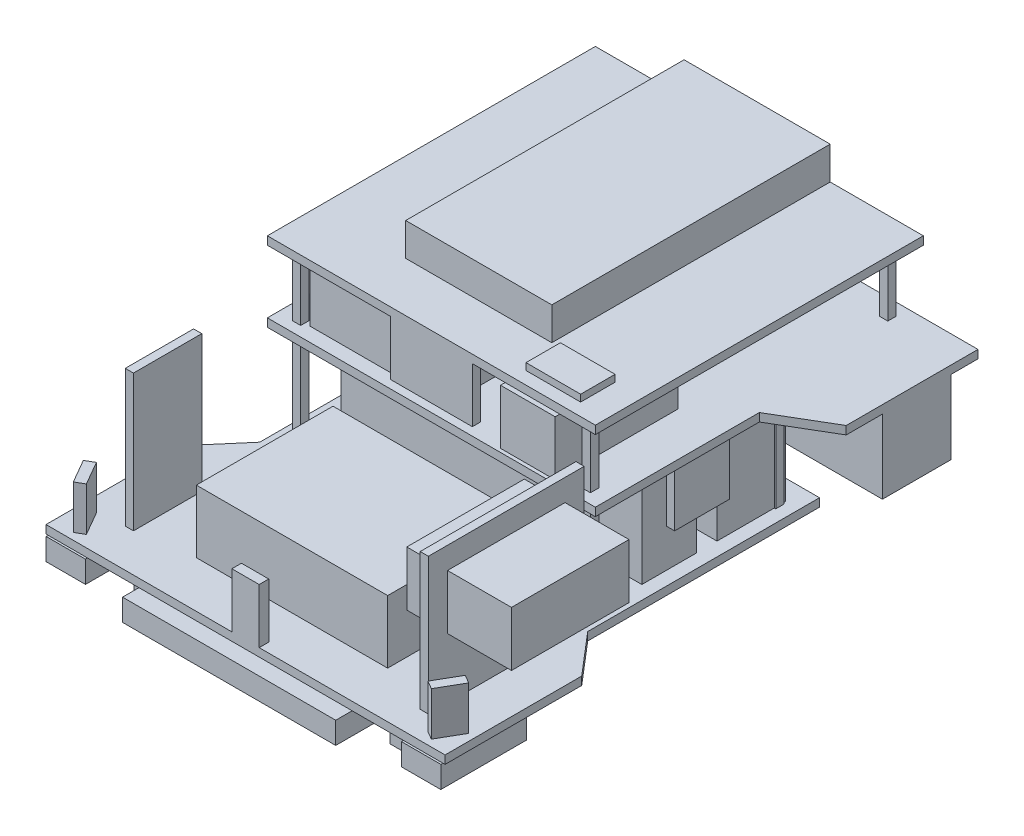
SolidWorks part; units mm, degrees
ref_plane "Front Plane" through (0, 0, 0) normal (0, 0, 1) x (1, 0, 0)
ref_plane "Top Plane" through (0, 0, 0) normal (0, 1, 0) x (1, 0, 0)
ref_plane "Right Plane" through (0, 0, 0) normal (1, 0, 0) x (0, 0, -1)
sketch "Sketch1" plane through (0, 0, 0) normal (0, 1, 0) x (1, 0, 0)
  line L0 (-73, -25) -> (-60, -9.8013)
  line L1 (60, -75) -> (-60, -75)
  line L2 (60, -9.8013) -> (60, 75)
  line L3 (60, 75) -> (-60, 75)
  line L4 (-60, -9.8013) -> (-60, 75)
  line L5 (60, -75) -> (-60, 75) construction
  line L6 (60, 75) -> (-60, -75) construction
  line L7 (0, 0) -> (0, -75) construction
  line L9 (-60, -75) -> (-73, -75)
  line L10 (-73, -25) -> (-73, -75)
  line L11 (60, -75) -> (73, -75)
  line L12 (73, -25) -> (73, -75)
  line L13 (73, -25) -> (60, -9.8013)
  point P0 (0, 0)
  dimension "D1" = 150
  dimension "D2" = 120
  dimension "D3" = 50
  dimension "D4" = 13
  dimension "D5" = 20
extrude "Boss-Extrude1" add sketch "Sketch1" along normal blind 3
sketch "Sketch2" plane through (0, 3, 0) normal (0, 1, 0) x (1, 0, 0)
  line L0 (0, 0) -> (0, 75) construction
  line L1 (60, 75) -> (-60, 75) construction
  line L2 (-60, 75) -> (-60, -9.8013) construction
  line L4 (-54.525, -3.335) -> (-51.475, -3.335)
  line L5 (-54.525, -3.335) -> (-54.525, -0.285)
  line L6 (-54.525, -0.285) -> (-51.475, -0.285)
  line L7 (-51.475, -3.335) -> (-51.475, -0.285)
  line L8 (-54.525, -3.335) -> (-51.475, -0.285) construction
  line L9 (-54.525, -0.285) -> (-51.475, -3.335) construction
  line L10 (51.475, -3.335) -> (54.525, -3.335)
  line L11 (51.475, -3.335) -> (51.475, -0.285)
  line L12 (51.475, -0.285) -> (54.525, -0.285)
  line L13 (54.525, -3.335) -> (54.525, -0.285)
  line L14 (51.475, -3.335) -> (54.525, -0.285) construction
  line L15 (51.475, -0.285) -> (54.525, -3.335) construction
  line L16 (52.475, 63.475) -> (55.525, 63.475)
  line L17 (52.475, 63.475) -> (52.475, 66.525)
  line L18 (52.475, 66.525) -> (55.525, 66.525)
  line L19 (55.525, 63.475) -> (55.525, 66.525)
  line L20 (52.475, 63.475) -> (55.525, 66.525) construction
  line L21 (52.475, 66.525) -> (55.525, 63.475) construction
  line L22 (-55.525, 63.475) -> (-52.475, 63.475)
  line L23 (-55.525, 63.475) -> (-55.525, 66.525)
  line L24 (-55.525, 66.525) -> (-52.475, 66.525)
  line L25 (-52.475, 63.475) -> (-52.475, 66.525)
  line L26 (-55.525, 63.475) -> (-52.475, 66.525) construction
  line L27 (-55.525, 66.525) -> (-52.475, 63.475) construction
  circle A0 centre (-53, -1.81) radius 1.525 construction
  circle A1 centre (-54, 65) radius 1.525 construction
  circle A2 centre (53, -1.81) radius 1.525 construction
  circle A3 centre (54, 65) radius 1.525 construction
  dimension "D1" = 10
  dimension "D2" = 3.05
  dimension "D3" = 6
  dimension "D4" = 3.05
  dimension "D5" = 7
  dimension "D6" = 66.81
extrude "Boss-Extrude2" add sketch "Sketch2" along normal blind 35
sketch "Sketch3" plane through (0, 38, 0) normal (0, 1, 0) x (1, 0, 0)
  line L0 (0, 52.99) -> (0, 112.99) construction
  line L1 (-60, -7.01) -> (60, -7.01)
  line L2 (-60, -7.01) -> (-60, 112.99)
  line L3 (-60, 112.99) -> (60, 112.99)
  line L4 (60, -7.01) -> (60, 112.99)
  line L5 (-60, -7.01) -> (60, 112.99) construction
  line L6 (-60, 112.99) -> (60, -7.01) construction
  line L7 (-60, 112.99) -> (-80, 112.99)
  line L8 (-80, 112.99) -> (-80, 64.7803)
  line L9 (-80, 64.7803) -> (-60, 52.99)
  line L10 (80, 64.7803) -> (60, 52.99)
  line L11 (80, 112.99) -> (80, 64.7803)
  line L12 (60, 112.99) -> (80, 112.99)
  line L14 (-54.525, -0.285) -> (-54.525, -3.335) construction
  point P0 (0, 52.99)
  point P19 (-54.525, -1.81)
  dimension "D1" = 120
  dimension "D2" = 120
  dimension "D3" = 60
  dimension "D4" = 30.52
  dimension "D5" = 20
  dimension "D6" = 5.2
extrude "Boss-Extrude3" add sketch "Sketch3" along normal blind 3 contours L8 L9 L2 L7 | L1 L4 L3 L2 | L12 L4 L10 L11
sketch "Sketch4" plane through (0, 41, 0) normal (0, 1, 0) x (1, 0, 0)
  line L0 (0, 0) -> (0, 32.3428) construction
  line L1 (-54.525, -3.335) -> (-51.475, -3.335)
  line L2 (-54.525, -3.335) -> (-54.525, -0.285)
  line L3 (-54.525, -0.285) -> (-51.475, -0.285)
  line L4 (-51.475, -3.335) -> (-51.475, -0.285)
  line L5 (-54.525, -3.335) -> (-51.475, -0.285) construction
  line L6 (-54.525, -0.285) -> (-51.475, -3.335) construction
  line L7 (-60, -7.01) -> (60, -7.01) construction
  line L8 (-60, -7.01) -> (-60, 52.99) construction
  line L9 (80, 112.99) -> (-80, 112.99) construction
  line L10 (-54.525, 105.465) -> (-51.475, 105.465)
  line L11 (-54.525, 105.465) -> (-54.525, 108.515)
  line L12 (-54.525, 108.515) -> (-51.475, 108.515)
  line L13 (-51.475, 105.465) -> (-51.475, 108.515)
  line L14 (-54.525, 105.465) -> (-51.475, 108.515) construction
  line L15 (-54.525, 108.515) -> (-51.475, 105.465) construction
  line L16 (54.525, -0.285) -> (51.475, -3.335) construction
  line L17 (54.525, -3.335) -> (51.475, -0.285) construction
  line L18 (51.475, -3.335) -> (51.475, -0.285)
  line L19 (54.525, -0.285) -> (51.475, -0.285)
  line L20 (54.525, -3.335) -> (54.525, -0.285)
  line L21 (54.525, -3.335) -> (51.475, -3.335)
  line L22 (54.525, 108.515) -> (51.475, 105.465) construction
  line L23 (54.525, 105.465) -> (51.475, 108.515) construction
  line L24 (51.475, 105.465) -> (51.475, 108.515)
  line L25 (54.525, 108.515) -> (51.475, 108.515)
  line L26 (54.525, 105.465) -> (54.525, 108.515)
  line L27 (54.525, 105.465) -> (51.475, 105.465)
  point P0 (-53, -1.81)
  point P12 (-53, 106.99)
  point P24 (53, -1.81)
  point P29 (53, 106.99)
  dimension "D1" = 3.05
  dimension "D2" = 5.2
  dimension "D3" = 7
  dimension "D4" = 6
extrude "Boss-Extrude4" add sketch "Sketch4" along normal blind 23
sketch "Sketch6" plane through (0, 64, 0) normal (0, 1, 0) x (1, 0, 0)
  line L0 (60, -7.01) -> (-60, -7.01)
  line L1 (60, -7.01) -> (60, 112.99)
  line L2 (-60, -7.01) -> (-60, 112.99)
  line L3 (60, 112.99) -> (-60, 112.99)
  line L4 (80, 112.99) -> (-80, 112.99) construction
extrude "Boss-Extrude5" add sketch "Sketch6" along normal blind 3
sketch "Sketch7" plane through (0, 38, 0) normal (0, -1, 0) x (1, 0, 0)
  line L0 (-80, -78.03) -> (-80, -103.03)
  line L1 (-80, -78.03) -> (-12, -78.03)
  line L2 (-80, -103.03) -> (-12, -103.03)
  line L3 (-12, -78.03) -> (-12, -103.03)
  line L4 (-80, -112.99) -> (-80, -64.7803) construction
  line L5 (0, 0) -> (0, -39.6137) construction
  line L6 (12, -78.03) -> (12, -103.03)
  line L7 (80, -103.03) -> (12, -103.03)
  line L8 (80, -78.03) -> (12, -78.03)
  line L9 (80, -78.03) -> (80, -103.03)
  line L10 (80, -112.99) -> (-80, -112.99) construction
  point P13 (-80, -90.53)
  dimension "D1" = 68
  dimension "D2" = 25
  dimension "D3" = 22.46
extrude "Boss-Extrude6" add sketch "Sketch7" along normal blind 27
sketch "Sketch9" plane through (0, 41, 0) normal (0, 1, 0) x (1, 0, 0)
  line L0 (-60, -7.01) -> (-60, 52.99) construction
  line L1 (-30.05, 45.88) -> (27.95, 45.88)
  line L2 (-30.05, 45.88) -> (-30.05, 105.88)
  line L3 (-30.05, 105.88) -> (27.95, 105.88)
  line L4 (27.95, 45.88) -> (27.95, 105.88)
  line L5 (-30.05, 45.88) -> (27.95, 105.88) construction
  line L6 (-30.05, 105.88) -> (27.95, 45.88) construction
  line L7 (80, 112.99) -> (-80, 112.99) construction
  line L8 (0, 0) -> (0, 23.7636) construction
  line L13 (-60, 112.99) -> (-60, -7.01) construction
  line L15 (-60, -7.01) -> (60, -7.01) construction
  line L16 (44, -5.71) -> (24, -5.71)
  line L17 (24, 39.29) -> (24, -5.71)
  line L18 (44, 39.29) -> (24, 39.29)
  line L19 (44, 39.29) -> (44, -5.71)
  line L20 (-60, -7.01) -> (60, -7.01) construction
  line L21 (-49.66, 28.16) -> (0.34, 28.16)
  line L22 (-49.66, 28.16) -> (-49.66, -1.84)
  line L23 (-49.66, -1.84) -> (0.34, -1.84)
  line L24 (0.34, 28.16) -> (0.34, -1.84)
  line L25 (-49.66, 28.16) -> (0.34, -1.84) construction
  line L26 (-49.66, -1.84) -> (0.34, 28.16) construction
  line L27 (60, -7.01) -> (60, 112.99) construction
  point P0 (-1.05, 75.88)
  point P23 (-24.66, 13.16)
  dimension "D1" = 58
  dimension "D2" = 29.95
  dimension "D3" = 60
  dimension "D4" = 7.11
  dimension "D5" = 10.34
  dimension "D6" = 1.3
  dimension "D7" = 16
  dimension "D8" = 20
  dimension "D9" = 5.17
  dimension "D10" = 50
  dimension "D11" = 30
  dimension "D12" = 45
extrude "Boss-Extrude7" add sketch "Sketch9" along normal blind 20
sketch "Sketch10" plane through (0, 67, 0) normal (0, 1, 0) x (1, 0, 0)
  line L0 (-27.54, 112.99) -> (25.92, 112.99)
  line L1 (-27.54, 112.99) -> (-27.54, 11.14)
  line L2 (25.92, 112.99) -> (25.92, 11.14)
  line L3 (-27.54, 11.14) -> (25.92, 11.14)
  line L4 (60, 112.99) -> (-60, 112.99) construction
  line L5 (-60, 112.99) -> (-60, -7.01) construction
  dimension "D1" = 32.46
  dimension "D2" = 53.46
  dimension "D3" = 101.85
extrude "Boss-Extrude8" add sketch "Sketch10" along normal blind 12
sketch "Sketch11" plane through (0, 3, 0) normal (0, 1, 0) x (1, 0, 0)
  line L1 (-55, 35) -> (55, 35)
  line L2 (-55, 35) -> (-55, 15)
  line L3 (-55, 15) -> (55, 15)
  line L4 (55, 35) -> (55, 15)
  line L5 (-55, 35) -> (55, 15) construction
  line L6 (-55, 15) -> (55, 35) construction
  point P0 (0, 25)
  dimension "D1" = 110
  dimension "D2" = 20
  dimension "D3" = 25
extrude "Boss-Extrude9" add sketch "Sketch11" along normal blind 32
sketch "Sketch12" plane through (0, 3, 0) normal (0, 1, 0) x (1, 0, 0)
  line L1 (-55, 42.5) -> (55, 42.5)
  line L2 (-55, 42.5) -> (-55, 67.5)
  line L3 (-55, 67.5) -> (55, 67.5)
  line L4 (55, 42.5) -> (55, 67.5)
  line L5 (-55, 42.5) -> (55, 67.5) construction
  line L6 (-55, 67.5) -> (55, 42.5) construction
  point P0 (0, 55)
  dimension "D1" = 110
  dimension "D2" = 25
  dimension "D3" = 55
extrude "Boss-Extrude10" add sketch "Sketch12" along normal blind 34
sketch "Sketch13" plane through (0, 67, 0) normal (0, 1, 0) x (1, 0, 0)
  line L0 (60, -7.01) -> (60, 112.99) construction
  line L1 (30, -2.39) -> (50, -2.39)
  line L2 (30, -2.39) -> (30, 10.21)
  line L3 (30, 10.21) -> (50, 10.21)
  line L4 (50, -2.39) -> (50, 10.21)
  line L5 (30, -2.39) -> (50, 10.21) construction
  line L6 (30, 10.21) -> (50, -2.39) construction
  line L7 (-60, -7.01) -> (60, -7.01) construction
  point P0 (40, 3.91)
  dimension "D1" = 20
  dimension "D2" = 12.6
  dimension "D3" = 10
  dimension "D4" = 4.62
extrude "Boss-Extrude11" add sketch "Sketch13" along normal blind 2.5
sketch "Sketch14" plane through (0, 38, 0) normal (0, 1, 0) x (1, 0, 0)
  line L0 (60, -7.01) -> (60, 112.99) construction
  line L1 (59, 42.99) -> (56, 42.99)
  line L2 (59, 42.99) -> (59, 22.99)
  line L3 (59, 22.99) -> (56, 22.99)
  line L4 (56, 42.99) -> (56, 22.99)
  line L5 (59, 42.99) -> (56, 22.99) construction
  line L6 (59, 22.99) -> (56, 42.99) construction
  line L7 (-60, -7.01) -> (60, -7.01) construction
  line L8 (0, 0) -> (0, 51.8866) construction
  line L9 (-59, 22.99) -> (-56, 42.99) construction
  line L10 (-59, 42.99) -> (-56, 22.99) construction
  line L11 (-56, 42.99) -> (-56, 22.99)
  line L12 (-59, 22.99) -> (-56, 22.99)
  line L13 (-59, 42.99) -> (-59, 22.99)
  line L14 (-59, 42.99) -> (-56, 42.99)
  point P0 (57.5, 32.99)
  point P16 (-57.5, 32.99)
  point P17 (-57.5, 47.99)
  dimension "D1" = 1
  dimension "D2" = 3
  dimension "D3" = 20
  dimension "D4" = 30
extrude "Boss-Extrude12" add sketch "Sketch14" against normal blind 20
sketch "Sketch15" plane through (0, 3, 0) normal (0, 1, 0) x (1, 0, 0)
  line L6 (0, 0) -> (0, -32.3725) construction
  line L11 (65.5, -72.5) -> (62.4689, -70.75)
  line L12 (62.4689, -70.75) -> (67.4689, -62.0897)
  line L13 (67.4689, -62.0897) -> (70.5, -63.8397)
  line L14 (70.5, -63.8397) -> (65.5, -72.5)
  line L15 (-70.5, -63.8397) -> (-65.5, -72.5)
  line L16 (-67.4689, -62.0897) -> (-70.5, -63.8397)
  line L17 (-62.4689, -70.75) -> (-67.4689, -62.0897)
  line L18 (-65.5, -72.5) -> (-62.4689, -70.75)
  line L19 (-73, -75) -> (73, -75) construction
  line L20 (73, -75) -> (73, -25) construction
  dimension "D1" = 3.5
  dimension "D2" = 10
  dimension "D3" = 2.5
  dimension "D4" = 2.5
  dimension "D5" = 60
extrude "Boss-Extrude13" add sketch "Sketch15" along normal blind 16
sketch "Sketch16" plane through (0, 3, 0) normal (0, 1, 0) x (1, 0, 0)
  line L0 (73, -75) -> (73, -25) construction
  line L1 (54, -8.1) -> (57, -8.1)
  line L2 (54, -8.1) -> (54, -65.1)
  line L3 (54, -65.1) -> (57, -65.1)
  line L4 (57, -8.1) -> (57, -65.1)
  line L5 (-73, -75) -> (73, -75) construction
  line L6 (-73, -25) -> (-73, -75) construction
  line L7 (-58, -36) -> (-55, -36)
  line L8 (-58, -36) -> (-58, -61)
  line L9 (-58, -61) -> (-55, -61)
  line L10 (-55, -36) -> (-55, -61)
  dimension "D1" = 19
  dimension "D2" = 3
  dimension "D3" = 57
  dimension "D4" = 9.9
  dimension "D5" = 15
  dimension "D6" = 3
  dimension "D7" = 25
  dimension "D8" = 14
extrude "Boss-Extrude14" add sketch "Sketch16" along normal blind 50
sketch "Sketch17" plane through (57, 0, 0) normal (1, 0, 0) x (0, 0, -1)
  line L0 (-65.1, 53) -> (-8.1, 53) construction
  line L1 (-58.1, 45) -> (-15.1, 45)
  line L2 (-58.1, 45) -> (-58.1, 25)
  line L3 (-58.1, 25) -> (-15.1, 25)
  line L4 (-15.1, 45) -> (-15.1, 25)
  line L6 (-65.1, 53) -> (-65.1, 3) construction
  dimension "D1" = 8
  dimension "D2" = 20
  dimension "D3" = 43
  dimension "D4" = 7
extrude "Boss-Extrude15" add sketch "Sketch17" along normal blind 23.4 and the other way blind 14.9
sketch "Sketch18" plane through (0, 0, 0) normal (0, -1, 0) x (1, 0, 0)
  line L0 (-73, 75) -> (73, 75) construction
  line L1 (-39, 56) -> (39, 56)
  line L2 (-39, 56) -> (-39, 81)
  line L3 (-39, 81) -> (39, 81)
  line L4 (39, 56) -> (39, 81)
  line L5 (0, 75) -> (0, 37.8257) construction
  line L6 (-72.2, 75.75) -> (-57.8, 75.75)
  line L7 (-72.2, 75.75) -> (-72.2, 44.45)
  line L8 (-72.2, 44.45) -> (-57.8, 44.45)
  line L9 (-57.8, 75.75) -> (-57.8, 44.45)
  line L10 (57.8, 75.75) -> (57.8, 44.45)
  line L11 (72.2, 44.45) -> (57.8, 44.45)
  line L12 (72.2, 75.75) -> (72.2, 44.45)
  line L13 (72.2, 75.75) -> (57.8, 75.75)
  line L14 (-73, 25) -> (-73, 75) construction
  point P4 (0, 56)
  dimension "D1" = 25
  dimension "D2" = 78
  dimension "D3" = 6
  dimension "D4" = 14.4
  dimension "D5" = 31.3
  dimension "D6" = 0.8
  dimension "D7" = 0.75
extrude "Boss-Extrude16" add sketch "Sketch18" along normal blind 8
sketch "Sketch20" plane through (0, 0, 0) normal (0, -1, 0) x (1, 0, 0)
  line L0 (0, 0) -> (0, 27.2161) construction
  line L1 (-51.89, 64) -> (-41.89, 64)
  line L2 (-51.89, 64) -> (-51.89, 54)
  line L3 (-51.89, 54) -> (-41.89, 54)
  line L4 (-41.89, 64) -> (-41.89, 54)
  line L9 (41.89, 64) -> (41.89, 54)
  line L10 (51.89, 54) -> (41.89, 54)
  line L11 (51.89, 64) -> (51.89, 54)
  line L12 (51.89, 64) -> (41.89, 64)
  line L14 (80, -78.03) -> (80, -64.7803) construction
  line L15 (39, 75) -> (57.8, 75) construction
  dimension "D1" = 10
  dimension "D2" = 10
  dimension "D3" = 11
  dimension "D4" = 28.11
extrude "Boss-Extrude18" add sketch "Sketch20" along normal blind 14.56
sketch "Sketch21" plane through (0, -14.56, 0) normal (0, -1, 0) x (1, 0, 0)
  line L14 (50.89, 55) -> (50.89, 63)
  line L15 (42.89, 55) -> (50.89, 55)
  line L16 (42.89, 63) -> (42.89, 55)
  line L17 (50.89, 63) -> (42.89, 63)
  line L18 (50.89, 55) -> (50.89, 63)
  line L19 (42.89, 55) -> (50.89, 55)
  line L20 (42.89, 63) -> (42.89, 55)
  line L21 (50.89, 63) -> (42.89, 63)
  line L32 (-42.89, 55) -> (-42.89, 63)
  line L33 (-50.89, 55) -> (-42.89, 55)
  line L34 (-50.89, 63) -> (-50.89, 55)
  line L35 (-42.89, 63) -> (-50.89, 63)
  line L36 (-42.89, 55) -> (-42.89, 63)
  line L37 (-50.89, 55) -> (-42.89, 55)
  line L38 (-50.89, 63) -> (-50.89, 55)
  line L39 (-42.89, 63) -> (-50.89, 63)
  dimension "D1" = 1
  dimension "D2" = 1
extrude "Cut-Extrude1" cut sketch "Sketch21" against normal blind 5
sketch "Sketch22" plane through (0, 3, 0) normal (0, 1, 0) x (1, 0, 0)
  line L1 (-5, -71.5) -> (5, -71.5)
  line L2 (-5, -71.5) -> (-5, -75)
  line L3 (-5, -75) -> (5, -75)
  line L4 (5, -71.5) -> (5, -75)
  line L6 (-39, -75) -> (39, -75) construction
  point P4 (0, -71.5)
  dimension "D1" = 10
  dimension "D3" = 3.5
extrude "Boss-Extrude19" add sketch "Sketch22" along normal blind 20
sketch "Sketch23" plane through (0, 64, 0) normal (0, -1, 0) x (1, 0, 0)
  line L0 (-60, 7.01) -> (60, 7.01) construction
  line L1 (-15, 7.01) -> (15, 7.01)
  line L2 (-15, 7.01) -> (-15, 4.01)
  line L3 (-15, 4.01) -> (15, 4.01)
  line L4 (15, 7.01) -> (15, 4.01)
  point P6 (0, 7.01)
  dimension "D1" = 30
  dimension "D2" = 3
extrude "Boss-Extrude20" add sketch "Sketch23" along normal blind 20
sketch "Sketch24" plane through (0, 3, 0) normal (0, 1, 0) x (1, 0, 0)
  line L0 (-73, -75) -> (-5, -75) construction
  line L1 (-35, -58) -> (35, -58)
  line L2 (-35, -58) -> (-35, -8)
  line L3 (-35, -8) -> (35, -8)
  line L4 (35, -58) -> (35, -8)
  line L5 (-35, -58) -> (35, -8) construction
  line L6 (-35, -8) -> (35, -58) construction
  point P0 (0, -33)
  dimension "D1" = 50
  dimension "D2" = 70
  dimension "D3" = 17
extrude "Boss-Extrude21" add sketch "Sketch24" along normal blind 23
